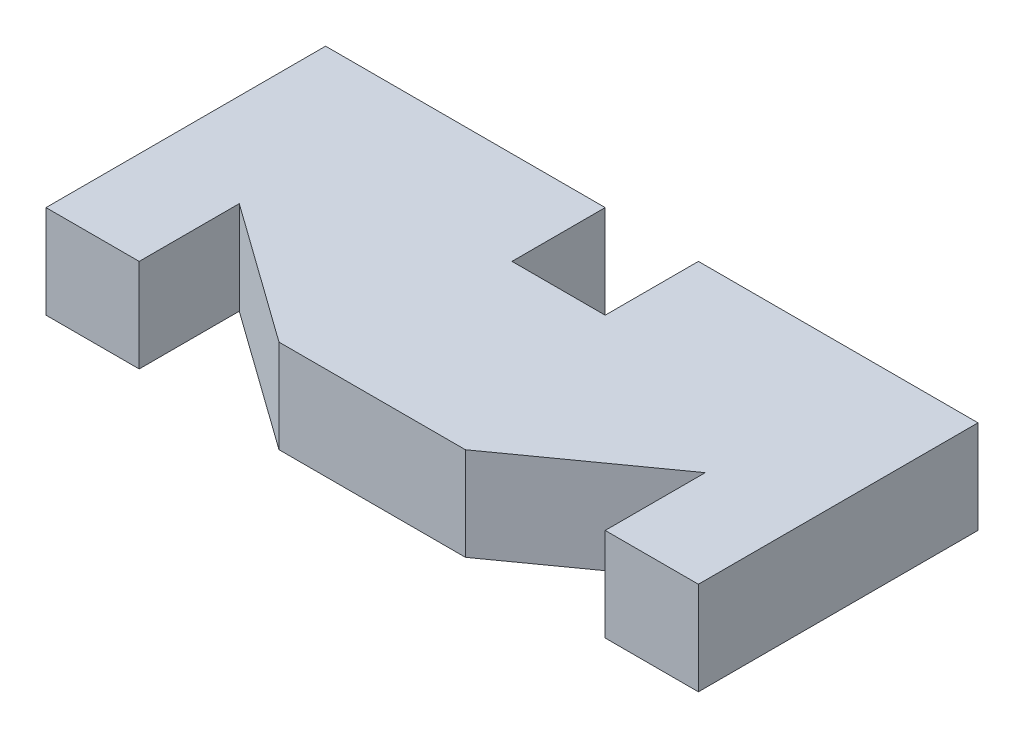
SolidWorks part; units mm, degrees
ref_plane "Front Plane" through (0, 0, 0) normal (0, 0, 1) x (1, 0, 0)
ref_plane "Top Plane" through (0, 0, 0) normal (0, 1, 0) x (1, 0, 0)
ref_plane "Right Plane" through (0, 0, 0) normal (1, 0, 0) x (0, 0, -1)
sketch "Sketch1" plane through (0, 0, 0) normal (0, 1, 0) x (1, 0, 0)
  line L2 (-35, 15) -> (-35, -15)
  line L4 (35, 15) -> (35, -15)
  line L5 (-35, 15) -> (35, -15) construction
  line L6 (-35, -15) -> (35, 15) construction
  line L15 (-35, 15) -> (-5, 15)
  line L16 (-5, 15) -> (-5, 5)
  line L21 (-5, 5) -> (5, 5)
  line L22 (5, 5) -> (5, 15)
  line L23 (5, 15) -> (35, 15)
  line L24 (-35, -15) -> (-25, -15)
  line L25 (-25, -15) -> (-25, -4.264)
  line L26 (-25, -4.264) -> (-10, -15)
  line L27 (-10, -15) -> (10, -15)
  line L28 (10, -15) -> (25, -4.264)
  line L29 (25, -4.264) -> (25, -15)
  line L30 (25, -15) -> (35, -15)
  point P0 (0, 0)
  dimension "D1" = 70
  dimension "D2" = 30
  dimension "D3" = 30
  dimension "D4" = 10
  dimension "D5" = 10
  dimension "D6" = 30
  dimension "D7" = 10
  dimension "D8" = 15
  dimension "D9" = 20
  dimension "D10" = 15
  dimension "D11" = 10
extrude "Boss-Extrude1" add sketch "Sketch1" along normal blind 10
